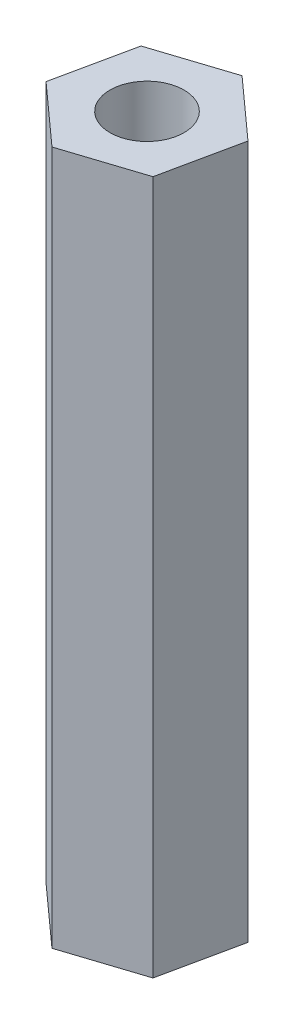
SolidWorks part; units mm, degrees
ref_plane "Front Plane" through (0, 0, 0) normal (0, 0, 1) x (1, 0, 0)
ref_plane "Top Plane" through (0, 0, 0) normal (0, 1, 0) x (1, 0, 0)
ref_plane "Right Plane" through (0, 0, 0) normal (1, 0, 0) x (0, 0, -1)
sketch "Sketch1" plane through (0, 0, 0) normal (0, 1, 0) x (1, 0, 0)
  line L1 (2.5748, -2.3174) -> (3.2943, 1.0712)
  line L2 (3.2943, 1.0712) -> (0.7195, 3.3886)
  line L3 (0.7195, 3.3886) -> (-2.5748, 2.3174)
  line L4 (-2.5748, 2.3174) -> (-3.2943, -1.0712)
  line L5 (-3.2943, -1.0712) -> (-0.7195, -3.3886)
  line L6 (-0.7195, -3.3886) -> (2.5748, -2.3174)
  circle A0 centre (0, 0) radius 1.6
  circle A1 centre (0, 0) radius 3 construction
  dimension "D1" = 3.2
  dimension "D2" = 6
extrude "Boss-Extrude1" add sketch "Sketch1" along normal blind 30
